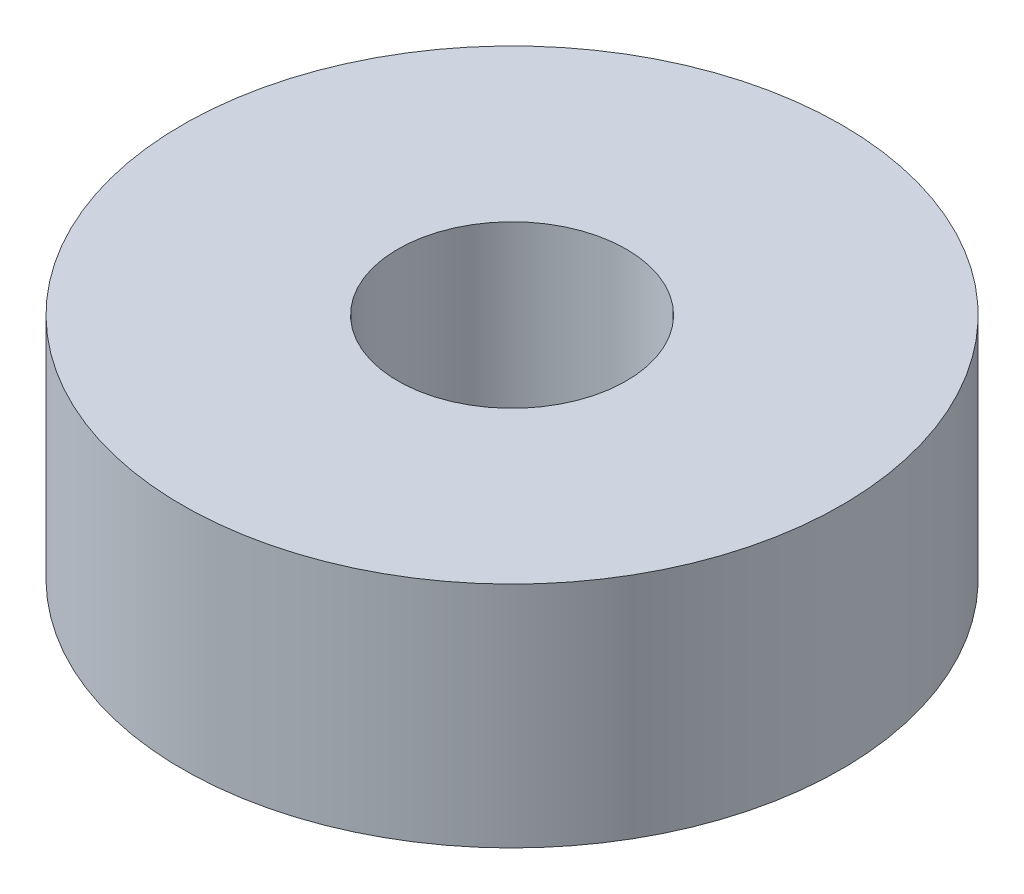
SolidWorks part; units mm, degrees
ref_plane "Front Plane" through (0, 0, 0) normal (0, 0, 1) x (1, 0, 0)
ref_plane "Top Plane" through (0, 0, 0) normal (0, 1, 0) x (1, 0, 0)
ref_plane "Right Plane" through (0, 0, 0) normal (1, 0, 0) x (0, 0, -1)
sketch "Sketch1" plane through (0, 0, 0) normal (0, 1, 0) x (1, 0, 0)
  circle A0 centre (0, 0) radius 9.525
  circle A1 centre (0, 0) radius 3.302
  dimension "D1" = 6.604
  dimension "D2" = 19.05
extrude "Boss-Extrude1" add sketch "Sketch1" along normal blind 6.604
